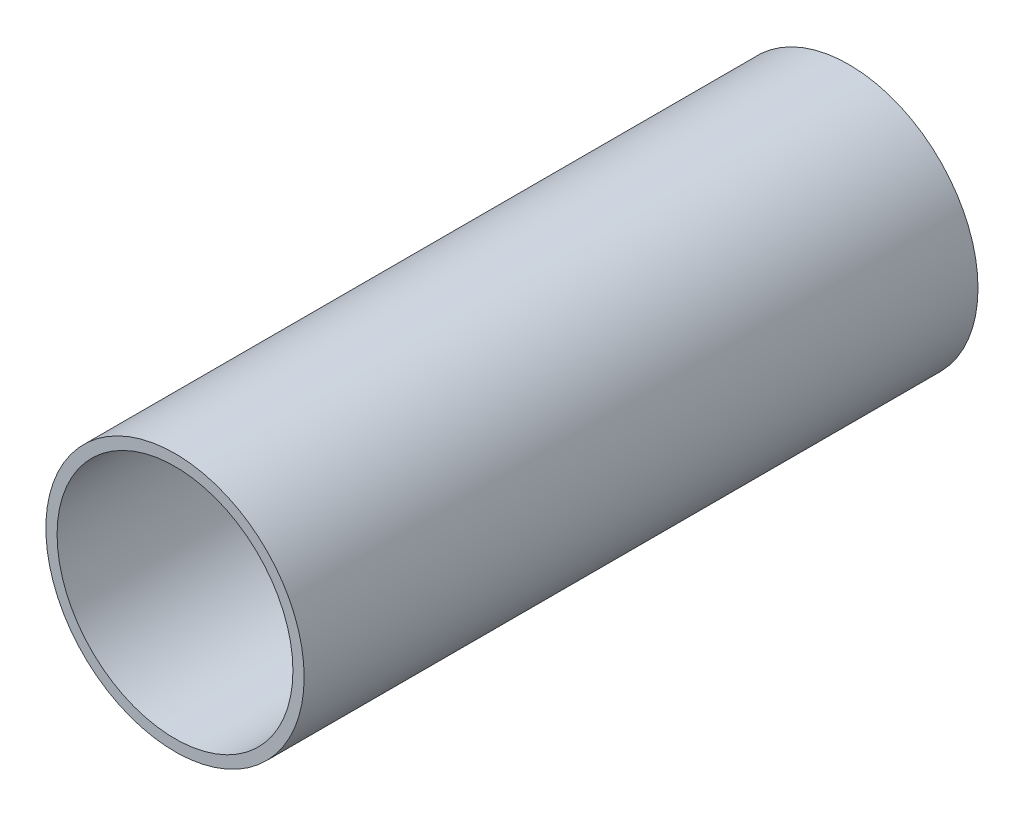
SolidWorks part; units mm, degrees
ref_plane "Plan de face" through (0, 0, 0) normal (0, 0, 1) x (1, 0, 0)
ref_plane "Plan de dessus" through (0, 0, 0) normal (0, 1, 0) x (1, 0, 0)
ref_plane "Plan de droite" through (0, 0, 0) normal (1, 0, 0) x (0, 0, -1)
sketch "Esquisse1" plane through (0, 0, 0) normal (0, 0, 1) x (1, 0, 0)
  circle A0 centre (0, 0) radius 52.5
  circle A1 centre (0, 0) radius 57.5
  dimension "D1" = 115
  dimension "D2" = 5
extrude "Boss.-Extru.1" add sketch "Esquisse1" along normal blind 300
